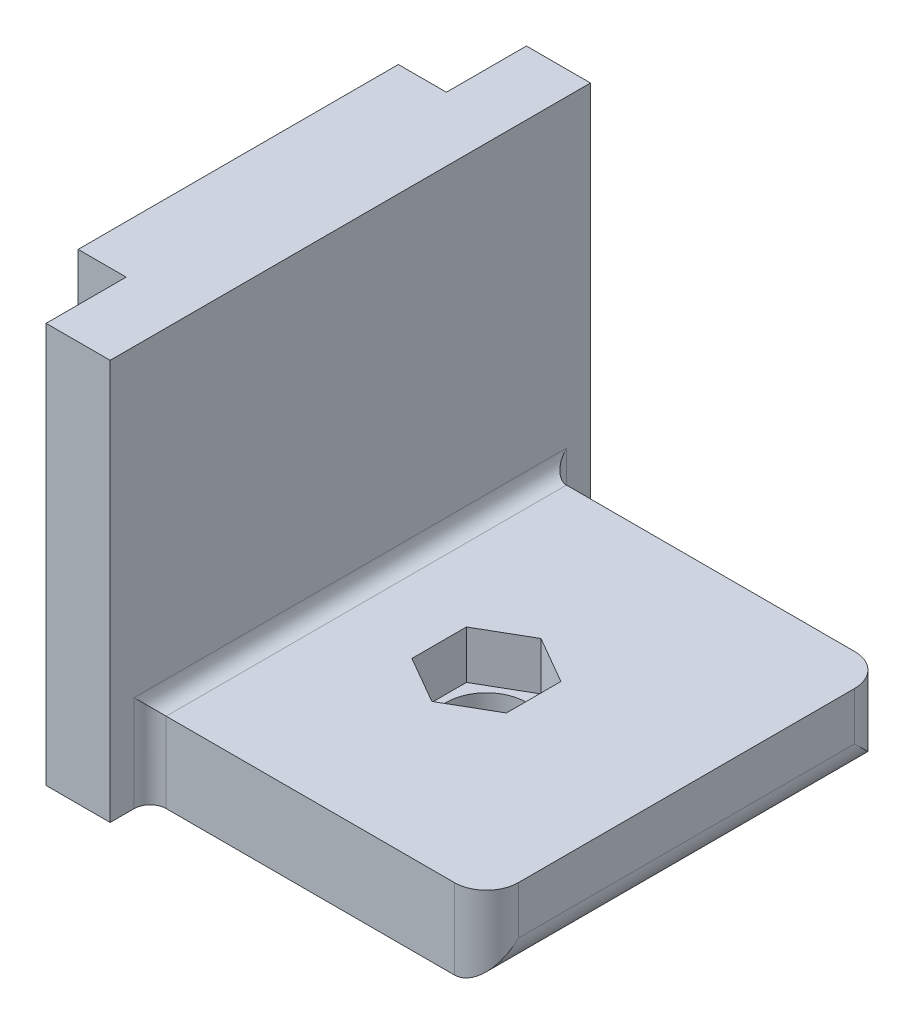
SolidWorks part; units mm, degrees
ref_plane "Front Plane" through (0, 0, 0) normal (0, 0, 1) x (1, 0, 0)
ref_plane "Top Plane" through (0, 0, 0) normal (0, 1, 0) x (1, 0, 0)
ref_plane "Right Plane" through (0, 0, 0) normal (1, 0, 0) x (0, 0, -1)
sketch "Sketch1" plane through (0, 0, 0) normal (0, 1, 0) x (1, 0, 0)
  line L0 (-12.5, 45) -> (-21.5, 45)
  line L1 (-12.5, 45) -> (-12.5, -135)
  line L2 (-12.5, -135) -> (-21.5, -135)
  line L3 (-21.5, 45) -> (-21.5, -135)
  line L4 (-12.5, 0) -> (12.5, 0) construction
  line L5 (-12.5, 10) -> (-15.5, 10)
  line L6 (-12.5, 10) -> (-12.5, -10)
  line L7 (-12.5, -10) -> (-15.5, -10)
  line L8 (-15.5, 10) -> (-15.5, -10)
  line L9 (-12.5, -15) -> (-8.5, -15)
  line L10 (-12.5, -15) -> (-12.5, 15)
  line L11 (-12.5, 15) -> (-8.5, 15)
  line L12 (-8.5, -15) -> (-8.5, 15)
  line L13 (-8.5, 12.5) -> (12.5, 12.5)
  line L14 (-8.5, 12.5) -> (-8.5, -12.5)
  line L15 (-8.5, -12.5) -> (12.5, -12.5)
  line L16 (12.5, 12.5) -> (12.5, -12.5)
  line L17 (-12.5, -12.5) -> (-12.5, 12.5)
  line L18 (-10, -10) -> (10, -10)
  line L19 (-10, -10) -> (-10, 10)
  line L20 (-10, 10) -> (10, 10)
  line L21 (10, -10) -> (10, 10)
  line L22 (-10, -10) -> (10, 10) construction
  line L23 (-10, 10) -> (10, -10) construction
  line L24 (-12.5, 12.5) -> (12.5, 12.5)
  line L25 (12.5, -12.5) -> (12.5, 12.5)
  line L26 (-12.5, -12.5) -> (12.5, -12.5)
  line L27 (2.95, 1.7032) -> (0, 3.4064)
  line L28 (2.75, 1.5877) -> (0, 3.1754) construction
  line L29 (0, 3.1754) -> (-2.75, 1.5877) construction
  line L30 (-2.75, 1.5877) -> (-2.75, -1.5877) construction
  line L31 (-2.75, -1.5877) -> (0, -3.1754) construction
  line L32 (0, -3.1754) -> (2.75, -1.5877) construction
  line L33 (2.75, -1.5877) -> (2.75, 1.5877) construction
  line L34 (0, 3.4064) -> (-2.95, 1.7032)
  line L35 (-2.95, 1.7032) -> (-2.95, -1.7032)
  line L36 (-2.95, -1.7032) -> (0, -3.4064)
  line L37 (0, -3.4064) -> (2.95, -1.7032)
  line L38 (2.95, -1.7032) -> (2.95, 1.7032)
  circle A0 centre (0, 0) radius 2.5
  circle A1 centre (0, 0) radius 6.5
  circle A2 centre (0, 0) radius 2.75 construction
  point P21 (0, 0)
sketch "Sketch2" plane through (0, 0, 0) normal (0, 1, 0) x (1, 0, 0)
  line L0 (-8.5, -12.5) -> (12.5, -12.5) construction
  line L1 (12.5, 12.5) -> (12.5, -12.5) construction
  line L2 (-8.5, 12.5) -> (12.5, 12.5) construction
  line L3 (-12.5, 10) -> (-15.5, 10) construction
  line L4 (-15.5, 10) -> (-15.5, -10) construction
  line L5 (-12.5, -10) -> (-15.5, -10) construction
  line L6 (-12.5, -15) -> (-8.5, -15) construction
  line L7 (-12.5, 45) -> (-12.5, -135) construction
  line L8 (-8.5, -15) -> (-8.5, 15) construction
  line L9 (-12.5, 15) -> (-8.5, 15) construction
  line L10 (-8.5, -12.5) -> (12.5, -12.5)
  line L11 (12.5, 12.5) -> (12.5, -12.5)
  line L12 (-8.5, 12.5) -> (12.5, 12.5)
  line L13 (-12.5, 10) -> (-15.5, 10)
  line L14 (-15.5, 10) -> (-15.5, -10)
  line L15 (-12.5, -10) -> (-15.5, -10)
  line L16 (-12.5, -15) -> (-8.5, -15)
  line L17 (-12.5, 15) -> (-12.5, 10)
  line L18 (-8.5, -15) -> (-8.5, -12.5)
  line L19 (-12.5, 15) -> (-8.5, 15)
  line L20 (-12.5, -10) -> (-12.5, -15)
  line L21 (-8.5, 12.5) -> (-8.5, 15)
extrude "Boss-Extrude1" add sketch "Sketch2" along normal blind 5
sketch "Sketch3" plane through (0, 5, 0) normal (0, 1, 0) x (1, 0, 0)
  line L0 (-15.5, 10) -> (-15.5, -10) construction
  line L1 (-12.5, -10) -> (-15.5, -10) construction
  line L3 (-12.5, 10) -> (-15.5, 10) construction
  line L4 (-12.5, 15) -> (-8.5, 15) construction
  line L5 (-8.5, -15) -> (-8.5, 15) construction
  line L6 (-12.5, -15) -> (-8.5, -15) construction
  line L7 (-12.5, -15) -> (-12.5, 15) construction
  line L8 (-15.5, 10) -> (-15.5, -10)
  line L9 (-12.5, -10) -> (-15.5, -10)
  line L11 (-12.5, 10) -> (-15.5, 10)
  line L12 (-12.5, 15) -> (-8.5, 15)
  line L13 (-8.5, -15) -> (-8.5, 15)
  line L14 (-12.5, -15) -> (-8.5, -15)
  line L15 (-12.5, -15) -> (-12.5, -10)
  line L16 (-12.5, 10) -> (-12.5, 15)
extrude "Boss-Extrude2" add sketch "Sketch3" along normal blind 20
sketch "Sketch4" plane through (0, 0, 0) normal (0, -1, 0) x (1, 0, 0)
  circle A0 centre (0, 0) radius 2.5 construction
  circle A1 centre (0, 0) radius 2.5
extrude "Cut-Extrude1" cut sketch "Sketch4" against normal through all both and the other way through all
fillet "Fillet1" radius 1 1 edges at (0, 0, -2.5)
fillet "Fillet2" radius 1 3 edges at (-8.5, 2.5, 12.5) (-8.5, 2.5, -12.5) (-8.5, 5, 0)
fillet "Fillet3" radius 2 3 edges at (12.5, 0, 0) (12.5, 2.5, -12.5) (12.5, 2.5, 12.5)
sketch "Sketch5" plane through (0, 5, 0) normal (0, 1, 0) x (1, 0, 0)
  line L0 (2.95, 1.7032) -> (0, 3.4064)
  line L1 (2.75, -1.5877) -> (2.75, 1.5877) construction
  line L2 (2.75, 1.5877) -> (0, 3.1754) construction
  line L3 (0, 3.1754) -> (-2.75, 1.5877) construction
  line L4 (-2.75, 1.5877) -> (-2.75, -1.5877) construction
  line L5 (-2.75, -1.5877) -> (0, -3.1754) construction
  line L6 (0, -3.1754) -> (2.75, -1.5877) construction
  line L7 (0, 3.4064) -> (-2.95, 1.7032)
  line L8 (-2.95, 1.7032) -> (-2.95, -1.7032)
  line L9 (-2.95, -1.7032) -> (0, -3.4064)
  line L10 (0, -3.4064) -> (2.95, -1.7032)
  line L11 (2.95, -1.7032) -> (2.95, 1.7032)
  circle A0 centre (0, 0) radius 2.75 construction
  dimension "D1" = 5.5
  dimension "D2" = 0.2
extrude "Cut-Extrude2" cut sketch "Sketch5" against normal blind 3
